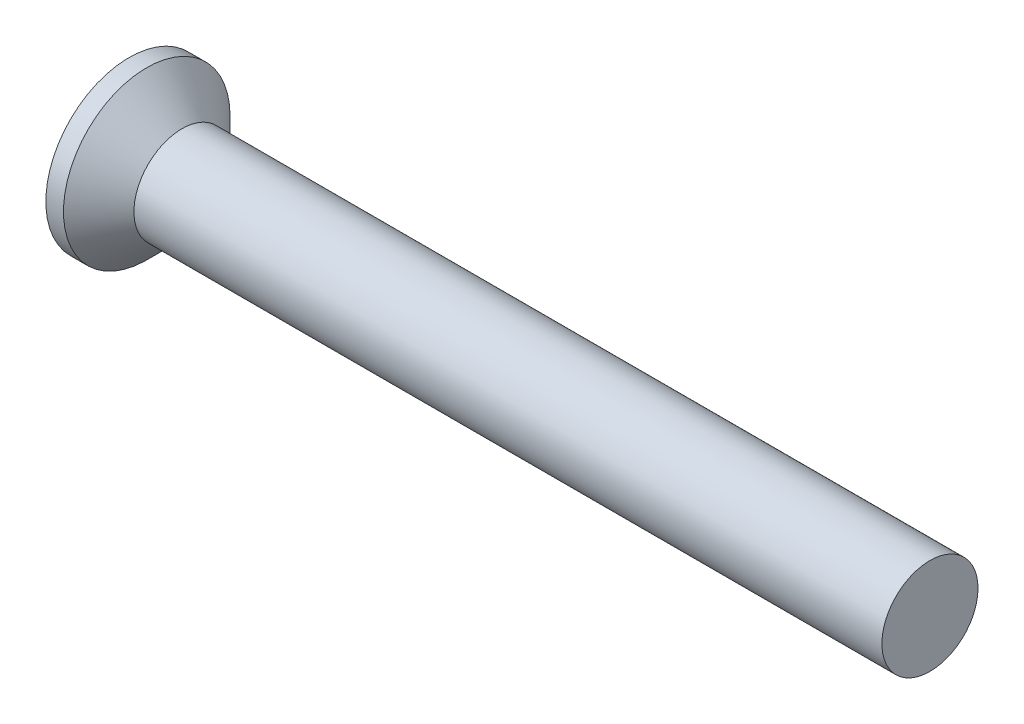
SolidWorks part; units mm, degrees
ref_plane "Front" through (0, 0, 0) normal (0, 0, 1) x (1, 0, 0)
ref_plane "Top" through (0, 0, 0) normal (0, 1, 0) x (1, 0, 0)
ref_plane "Right" through (0, 0, 0) normal (1, 0, 0) x (0, 0, -1)
other "Configuration Table"
sketch "Sketch1" plane through (0, 0, 0) normal (0, 0, 1) x (1, 0, 0)
  line L0 (25, 1.5) -> (2.65, 1.5)
  line L1 (2.65, 1.5) -> (1.65, 1.5)
  line L2 (1.65, 1.5) -> (0.55, 2.6)
  line L3 (0.55, 2.6) -> (0, 2.6)
  line L4 (25, 1.5) -> (25, 0)
  line L5 (4.5158, 0) -> (-89.8219, 0) construction
  line L6 (25, 0) -> (0, 0)
  line L7 (0, 2.6) -> (0, 0)
  dimension "d" = 3
  dimension "D1" = 45
  dimension "dk" = 5.2
  dimension "k" = 1.65
  dimension "l" = 25
  dimension "a" = 1
revolve "Base" add sketch "Sketch1" angle 360 about L5
cosmetic thread "ThreadCosmetic1" [suppressed] parameters "bb"=23.35, "THD_MINOR"=2.459
sketch "Sketch6" plane through (0, 0, 0) normal (1, 0, 0) x (0, 0, -1)
  line L0 (-1.9271, 0) -> (2.0512, 0) construction
  line L1 (0, 1.8651) -> (0, -2.0207) construction
  line L2 (0.32, 0.32) -> (0.32, 1.6)
  line L3 (0.32, 1.6) -> (-0.32, 1.6)
  line L4 (-0.32, 0.32) -> (-0.32, 1.6)
  line L5 (0.32, 0.32) -> (1.6, 0.32)
  line L6 (1.6, 0.32) -> (1.6, -0.32)
  line L7 (-1.6, 0.32) -> (-1.6, -0.32)
  line L8 (-0.32, 0.32) -> (-1.6, 0.32)
  line L9 (-0.32, -0.32) -> (-1.6, -0.32)
  line L10 (0.32, -0.32) -> (1.6, -0.32)
  line L11 (-0.32, -0.32) -> (-0.32, -1.6)
  line L12 (0.32, -1.6) -> (-0.32, -1.6)
  line L13 (0.32, -0.32) -> (0.32, -1.6)
  point P16 (-1.6, 0)
  point P17 (1.6, 0)
extrude "CrossRecess" cut sketch "Sketch6" along normal blind 0.825
draft "Draft9" type of draft neutral plane draft angle 30 faces to draft 4 face at (0.4125, 1.6, 0) face at (0.4125, 0, 1.6) face at (0.4125, -1.6, 0) face at (0.4125, 0, -1.6) neutral plane through (0, 2.6, 0) neutral plane normal (-1, 0, 0) parameters "D1"=30
fillet "Fillet5" radius 0.3 4 edges at (0.4125, -0.32, -0.32) (0.4125, 0.32, -0.32) (0.4125, 0.32, 0.32) (0.4125, -0.32, 0.32)
sketch "Sketch7" plane through (0, 0, 0) normal (1, 0, 0) x (0, 0, -1)
  line L0 (-2.0126, 0) -> (1.9757, 0) construction
  line L1 (0, 1.9314) -> (0, -2.0126) construction
  line L2 (0, 0) -> (1.5555, 1.5555) construction
  line L3 (0, 0.4782) -> (1.1314, 1.1314)
  line L4 (-1.5402, 1.5402) -> (0, 0) construction
  line L5 (0.4782, 0) -> (1.1314, 1.1314)
  line L6 (0, -0.4782) -> (1.1314, -1.1314)
  line L7 (0.4782, 0) -> (1.1314, -1.1314)
  line L8 (-0.4782, 0) -> (-1.1314, -1.1314)
  line L9 (0, -0.4782) -> (-1.1314, -1.1314)
  line L10 (-0.4782, 0) -> (-1.1314, 1.1314)
  line L11 (0, 0.4782) -> (-1.1314, 1.1314)
  dimension "D3" = 15
  dimension "m" = 3.2
extrude "Cut-Extrude3" [suppressed] cut sketch "Sketch7" along normal blind 10 draft 20
sketch "Sketch8" plane through (0, 0, 0) normal (0, 0, 1) x (1, 0, 0)
  line L0 (0, 1.7705) -> (-1.25, 1.5)
  line L1 (-1.25, 1.5) -> (1.65, 1.5)
  line L3 (25, -1.5) -> (25, 1.5) construction
  line L6 (1.65, 1.5) -> (1.65, 6.5)
  line L7 (1.65, 6.5) -> (0, 6.5)
  line L8 (0, 6.5) -> (0, 1.7705)
  line L9 (62.4753, 0.2705) -> (52.9594, 0.2705) construction
  dimension "D1" = 5
  dimension "x" = 1.25
  dimension "d" = 3
  dimension "THD_MINOR" = 2.459
  dimension "b" = 25
sketch "Sketch9" plane through (0, 0, 0) normal (0, 0, 1) x (1, 0, 0)
  line L0 (25, 1.2657) -> (25.1353, 1.5)
  line L1 (25.1353, 1.5) -> (25.1353, 1.7705)
  line L2 (25.1353, 1.7705) -> (24.8648, 1.7705)
  line L3 (24.8648, 1.7705) -> (24.8648, 1.5)
  line L4 (24.8648, 1.5) -> (25, 1.2657)
  line L5 (0, 0) -> (73.843, 0) construction
  line L6 (25, -1.5) -> (25, 1.5) construction
  dimension "D1" = 3
  dimension "D2" = 0.2705
revolve "Cut-Revolve10" [suppressed] cut sketch "Sketch9" angle 360 about L5
pattern_linear "LPattern10" [suppressed] count 72 spacing 0.3246 along (1, 0, 0)
equation "\"D1@Sketch6\" = \"m@Sketch6\" / 5"
equation "\"D1@CrossRecess\" = \"k@Sketch1\" / 2"
equation "\"D1@Sketch9\" = \"d@Sketch1\""
equation "\"D2@Sketch9\" =  ( \"d@Sketch1\" - \"THD_MINOR@ThreadCosmetic1\" )  / 2"
equation "\"D3@LPattern10\" = \"D2@Sketch9\" * 1.2"
equation "\"D1@LPattern10\" = \"bb@ThreadCosmetic1\" / \"D3@LPattern10\" "
